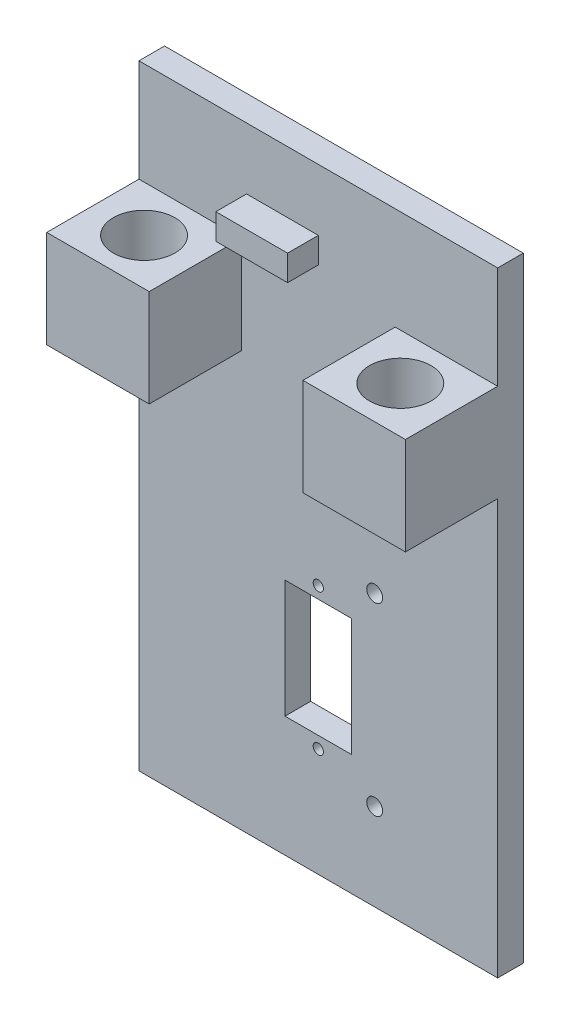
SolidWorks part; units mm, degrees
ref_plane "Front" through (0, 0, 0) normal (0, 0, 1) x (1, 0, 0)
ref_plane "Top" through (0, 0, 0) normal (0, 1, 0) x (1, 0, 0)
ref_plane "Right" through (0, 0, 0) normal (1, 0, 0) x (0, 0, -1)
sketch "Sketch1" plane through (0, 0, 0) normal (0, 0, 1) x (1, 0, 0)
  line L1 (-35, -60) -> (35, -60)
  line L2 (-35, -60) -> (-35, 60)
  line L3 (-35, 60) -> (35, 60)
  line L4 (35, -60) -> (35, 60)
  line L5 (-35, -60) -> (35, 60) construction
  line L6 (-35, 60) -> (35, -60) construction
  point P0 (0, 0)
  dimension "D1" = 120
  dimension "D2" = 70
extrude "Boss-Extrude1" add sketch "Sketch1" along normal blind 5
sketch "Sketch2" plane through (0, 0, 5) normal (0, 0, 1) x (1, 0, 0)
  line L0 (-35, 60) -> (-35, -60) construction
  line L1 (-35, 40) -> (-15, 40)
  line L2 (-35, 40) -> (-35, 21)
  line L3 (-35, 21) -> (-15, 21)
  line L4 (-15, 40) -> (-15, 21)
  line L5 (-35, 40) -> (-15, 21) construction
  line L6 (-35, 21) -> (-15, 40) construction
  line L7 (35, -60) -> (35, 60) construction
  line L8 (35, 40) -> (15, 40)
  line L9 (35, 40) -> (35, 21)
  line L10 (35, 21) -> (15, 21)
  line L11 (15, 40) -> (15, 21)
  line L12 (35, 40) -> (15, 21) construction
  line L13 (35, 21) -> (15, 40) construction
  line L14 (35, 60) -> (-35, 60) construction
  point P4 (-25, 30.5)
  point P11 (25, 30.5)
  dimension "D1" = 19
  dimension "D2" = 20
  dimension "D3" = 19
  dimension "D4" = 20
  dimension "D9" = 20
extrude "Boss-Extrude2" add sketch "Sketch2" along normal blind 18
sketch "Sketch3" plane through (0, 40, 0) normal (0, 1, 0) x (1, 0, 0)
  line L0 (-25, -23) -> (-25, -5) construction
  line L1 (-15, -23) -> (-35, -23) construction
  line L2 (-15, -5) -> (-35, -5) construction
  line L3 (25, -23) -> (25, -5) construction
  line L4 (35, -23) -> (15, -23) construction
  line L5 (35, -5) -> (15, -5) construction
  circle A0 centre (-25, -14) radius 6
  circle A1 centre (25, -14) radius 6
  dimension "D1" = 12
  dimension "D2" = 12
extrude "Cut-Extrude1" cut sketch "Sketch3" against normal through all
sketch "Sketch4" plane through (0, 0, 0) normal (0, 0, -1) x (-1, 0, 0)
  line L0 (35, 60) -> (35, -60) construction
  line L1 (-6.5, -36.5) -> (6.5, -36.5)
  line L2 (-6.5, -36.5) -> (-6.5, -13.5)
  line L3 (-6.5, -13.5) -> (6.5, -13.5)
  line L4 (6.5, -36.5) -> (6.5, -13.5)
  line L5 (-6.5, -36.5) -> (6.5, -13.5) construction
  line L6 (-6.5, -13.5) -> (6.5, -36.5) construction
  line L7 (-35, 60) -> (35, 60) construction
  circle A0 centre (0, -11.2) radius 1
  circle A1 centre (0, -38.8) radius 1
  point P0 (0, -25)
  dimension "D5" = 2
  dimension "D6" = 2.3
  dimension "D7" = 2
  dimension "D8" = 2.3
  dimension "D1" = 23
  dimension "D2" = 13
  dimension "D3" = 35
  dimension "D4" = 85
  dimension "D9" = 6.5
extrude "Cut-Extrude2" cut sketch "Sketch4" against normal up to next
sketch "Sketch5" plane through (0, 0, 5) normal (0, 0, 1) x (1, 0, 0)
  line L5 (-35, 60) -> (-35, 40) construction
  line L6 (-14, 48) -> (0, 48)
  line L8 (-14, 48) -> (-14, 43)
  line L9 (-14, 43) -> (0, 43)
  line L10 (0, 48) -> (0, 43)
  line L11 (-14, 48) -> (0, 43) construction
  line L12 (-14, 43) -> (0, 48) construction
  line L13 (35, 60) -> (-35, 60) construction
  point P0 (-7, 45.5)
  dimension "D1" = 5
  dimension "D2" = 14
  dimension "D3" = 21
  dimension "D4" = 12
extrude "Boss-Extrude3" add sketch "Sketch5" along normal blind 6
sketch "Sketch6" plane through (0, 0, 0) normal (0, 0, -1) x (-1, 0, 0)
  line L0 (-35, -60) -> (-35, 60) construction
  line L1 (35, -60) -> (-35, -60) construction
  circle A0 centre (-11, -7) radius 1.55
  circle A1 centre (-11, -43) radius 1.55
  dimension "D1" = 3.1
  dimension "D2" = 3.1
  dimension "D3" = 24
  dimension "D4" = 17
  dimension "D5" = 36
extrude "Cut-Extrude3" cut sketch "Sketch6" against normal through all
